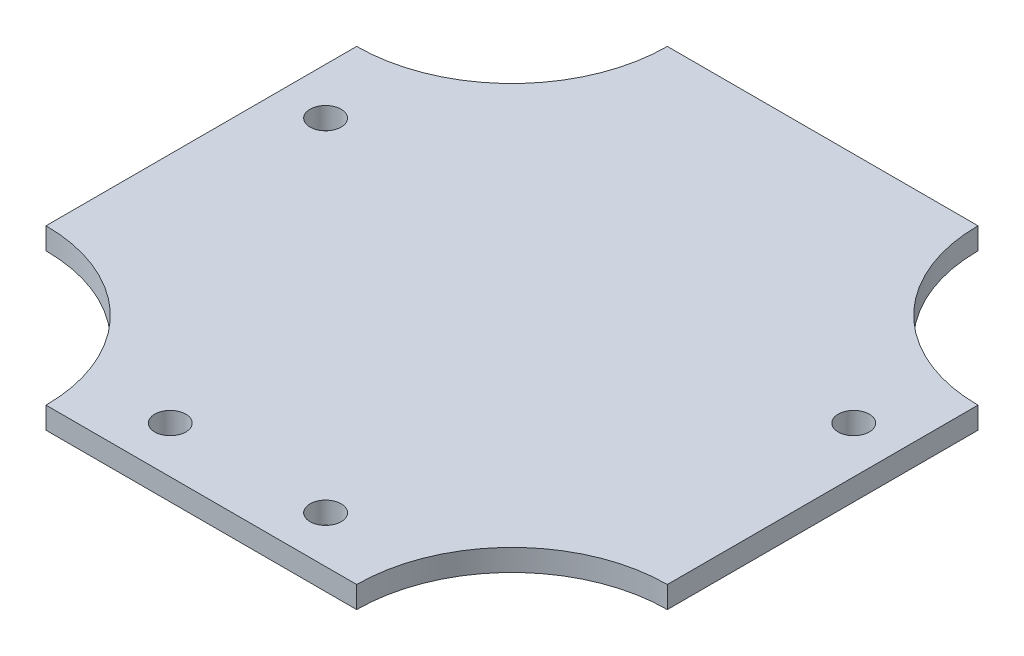
SolidWorks part; units mm, degrees
ref_plane "Front Plane" through (0, 0, 0) normal (0, 0, 1) x (1, 0, 0)
ref_plane "Top Plane" through (0, 0, 0) normal (0, 1, 0) x (1, 0, 0)
ref_plane "Right Plane" through (0, 0, 0) normal (1, 0, 0) x (0, 0, -1)
sketch "Sketch1" plane through (0, 0, 0) normal (0, 1, 0) x (1, 0, 0)
  line L1 (-50, 100) -> (50, 100)
  line L2 (-100, 50) -> (-100, -50)
  line L3 (-50, -100) -> (50, -100)
  line L4 (100, 50) -> (100, -50)
  line L5 (-64.6447, 64.6447) -> (64.6447, -64.6447) construction
  line L6 (-64.6447, -64.6447) -> (64.6447, 64.6447) construction
  arc A0 (-100, 50) -> (-50, 100) centre (-100, 100) ccw
  arc A2 (-100, -50) -> (-50, -100) centre (-100, -100) cw
  arc A3 (50, -100) -> (100, -50) centre (100, -100) cw
  arc A4 (50, 100) -> (100, 50) centre (100, 100) ccw
  circle A5 centre (-85, 25) radius 5
  circle A6 centre (85, 25) radius 5
  circle A7 centre (-25, -85) radius 5
  circle A8 centre (25, -85) radius 5
  point P0 (0, 0)
  point P6 (-100, 50)
  point P7 (-50, 100)
  point P8 (-100, 50)
  point P11 (-100, -50)
  point P12 (-50, -100)
  point P13 (100, 50)
  point P14 (50, 100)
  point P15 (50, -100)
  point P16 (-100, -50)
  point P17 (-50, -100)
  point P18 (50, -100)
  point P19 (-50, -100)
  point P20 (100, -50)
  point P21 (50, 100)
  point P22 (100, 50)
  point P33 (-25, -85)
  point P34 (-25, -85)
  point P35 (25, -85)
  point P36 (-25, -85)
  point P37 (85, 25)
  point P38 (-85, 25)
  point P47 (0, 0)
  dimension "D1" = 200
  dimension "D2" = 200
extrude "Boss-Extrude1" add sketch "Sketch1" along normal blind 7
